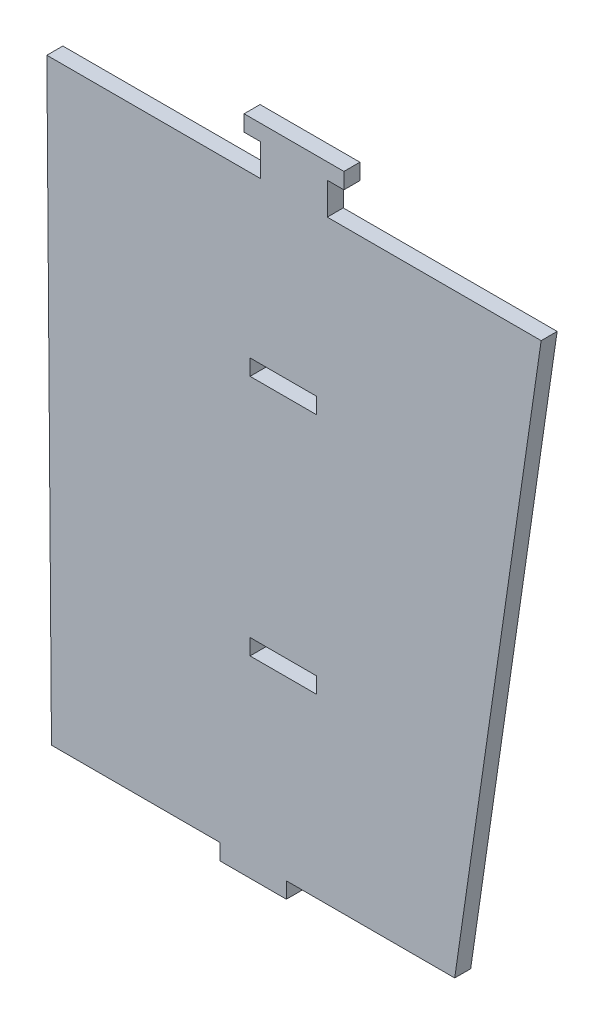
SolidWorks part; units mm, degrees
ref_plane "Front Plane" through (0, 0, 0) normal (0, 0, 1) x (1, 0, 0)
ref_plane "Top Plane" through (0, 0, 0) normal (0, 1, 0) x (1, 0, 0)
ref_plane "Right Plane" through (0, 0, 0) normal (1, 0, 0) x (0, 0, -1)
sketch "Sketch1" plane through (0, 0, 0) normal (0, 0, 1) x (1, 0, 0)
  line L0 (-102.4778, -1.524) -> (-110.7264, -58.3143)
  line L1 (-129.2335, 1.524) -> (-130.821, 1.524)
  line L2 (-110.7264, -58.3143) -> (-126.7879, -58.3143)
  line L3 (-149.1994, -58.3143) -> (-149.6393, -1.524)
  line L4 (-149.6393, -1.524) -> (-129.2335, -1.524)
  line L5 (-126.0585, -1.524) -> (-126.0585, 1.524) construction
  line L6 (-133.1379, -58.3143) -> (-133.1379, -59.8383)
  line L7 (-126.7879, -58.3143) -> (-126.7879, -59.8383)
  line L8 (-122.8835, -1.524) -> (-122.8835, 1.524)
  line L9 (-133.1379, -59.8383) -> (-126.7879, -59.8383)
  line L10 (-133.1379, -58.3143) -> (-149.1994, -58.3143)
  line L11 (-129.2335, -1.524) -> (-129.2335, 1.524)
  line L12 (-121.296, 1.524) -> (-121.296, 3.048)
  line L14 (-122.8835, -1.524) -> (-102.4778, -1.524)
  line L15 (-130.821, 1.524) -> (-130.821, 3.048)
  line L16 (-121.296, 1.524) -> (-122.8835, 1.524)
  line L17 (-121.296, 3.048) -> (-130.821, 3.048)
extrude "Boss-Extrude1" add sketch "Sketch1" along normal blind 1.524
sketch "Sketch2" plane through (0, 0, 1.524) normal (0, 0, 1) x (1, 0, 0)
  line L0 (-127.0788, -39.941) -> (-127.0788, -41.465) construction
  line L1 (-123.9038, -39.941) -> (-123.9038, -41.465)
  line L2 (-127.0788, -16.84) -> (-127.0788, -18.364) construction
  line L3 (-130.2538, -16.84) -> (-130.2538, -18.364)
  line L4 (-123.9038, -16.84) -> (-123.9038, -18.364)
  line L5 (-130.2538, -16.84) -> (-123.9038, -16.84)
  line L6 (-130.2538, -18.364) -> (-123.9038, -18.364)
  line L7 (-130.2538, -39.941) -> (-123.9038, -39.941)
  line L8 (-130.2538, -39.941) -> (-130.2538, -41.465)
  line L9 (-130.2538, -41.465) -> (-123.9038, -41.465)
extrude "Cut-Extrude1" cut sketch "Sketch2" against normal blind 1.524
